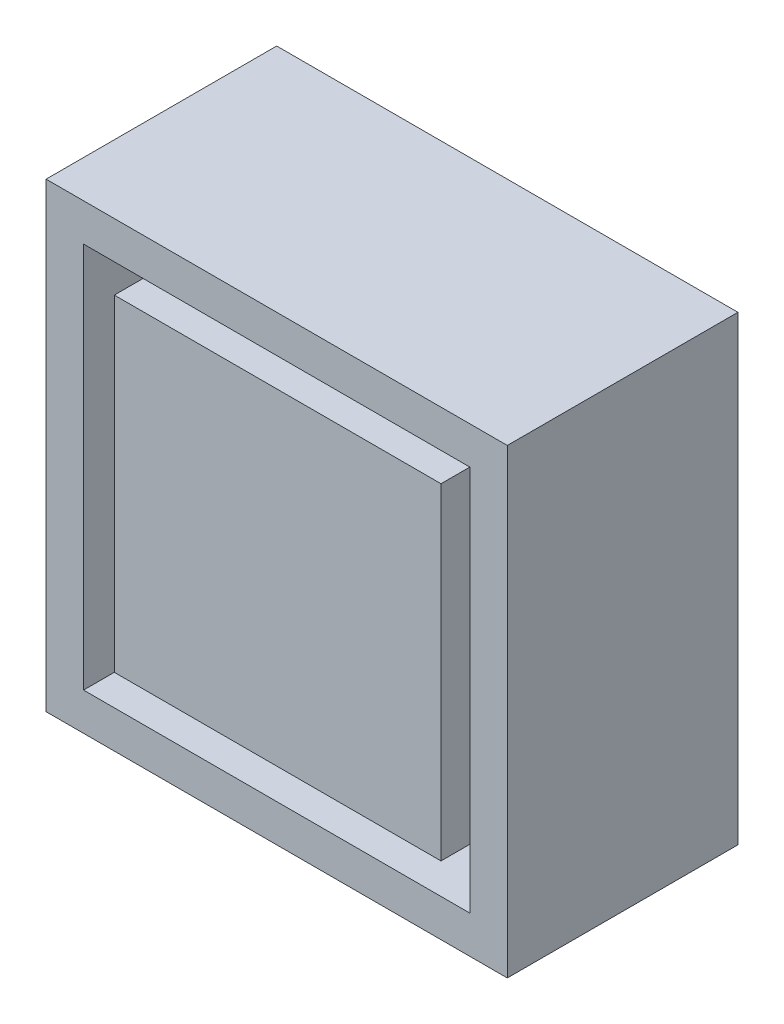
SolidWorks part; units mm, degrees
ref_plane "正面" through (0, 0, 0) normal (0, 0, 1) x (1, 0, 0)
ref_plane "平面" through (0, 0, 0) normal (0, 1, 0) x (1, 0, 0)
ref_plane "右側面" through (0, 0, 0) normal (1, 0, 0) x (0, 0, -1)
sketch "ｽｹｯﾁ1" plane through (0, 0, 0) normal (0, 0, 1) x (1, 0, 0)
  line L1 (0, 0) -> (24, 0)
  line L2 (0, 0) -> (0, 24)
  line L3 (0, 24) -> (24, 24)
  line L4 (24, 0) -> (24, 24)
  dimension "D1" = 24
  dimension "D2" = 24
extrude "ﾎﾞｽ - 押し出し5" add sketch "ｽｹｯﾁ1" along normal blind 12
shell "ｼｪﾙ2" thickness 1.95
sketch "ｽｹｯﾁ5" plane through (0, 0, 1.95) normal (0, 0, 1) x (1, 0, 0)
  line L0 (1.95, 22.05) -> (1.95, 1.95) construction
  line L1 (3.5, 20.5) -> (20.5, 20.5)
  line L2 (3.5, 20.5) -> (3.5, 3.5)
  line L3 (3.5, 3.5) -> (20.5, 3.5)
  line L4 (20.5, 20.5) -> (20.5, 3.5)
  line L5 (22.05, 1.95) -> (22.05, 22.05) construction
  line L6 (22.05, 22.05) -> (1.95, 22.05) construction
  line L7 (1.95, 1.95) -> (22.05, 1.95) construction
  dimension "D1" = 1.55
  dimension "D2" = 1.55
  dimension "D3" = 1.55
  dimension "D4" = 1.55
extrude "ﾎﾞｽ - 押し出し6" add sketch "ｽｹｯﾁ5" along normal blind 10
